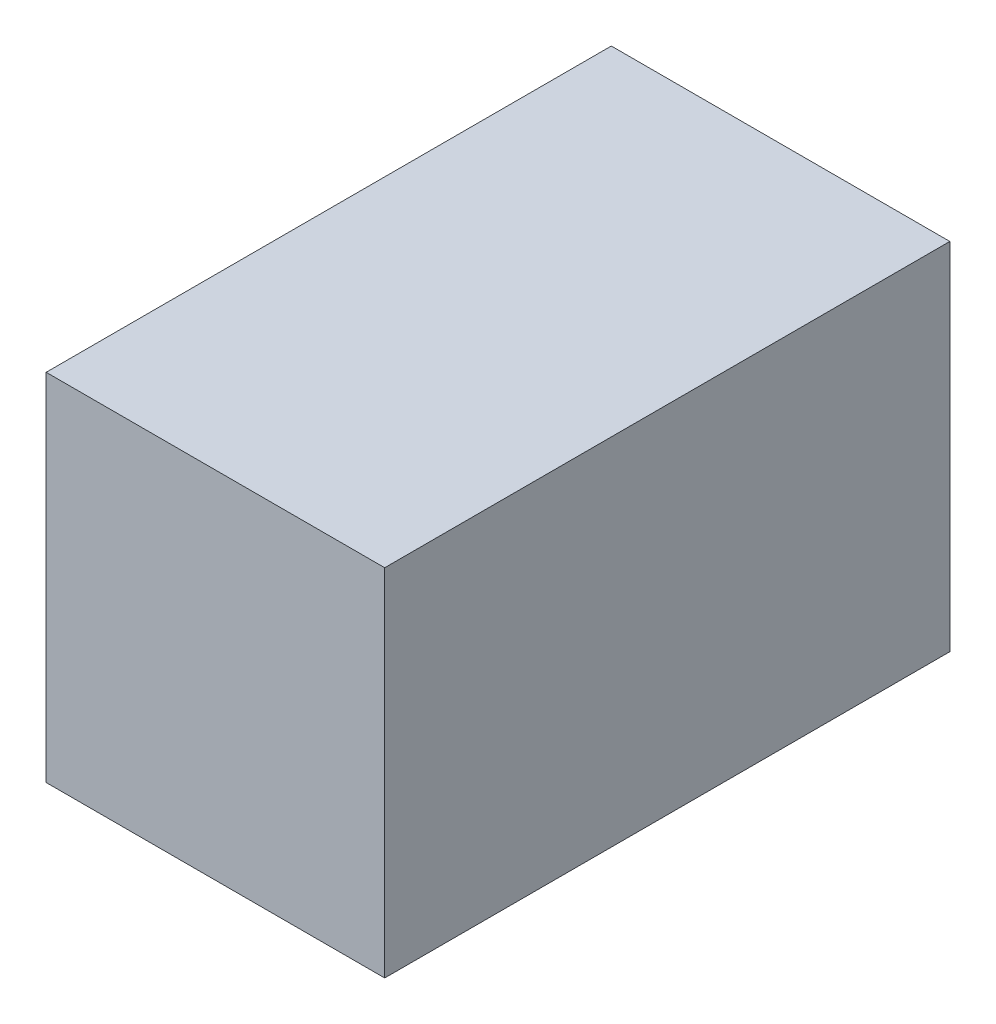
SolidWorks part; units mm, degrees
ref_plane "Front Plane" through (0, 0, 0) normal (0, 0, 1) x (1, 0, 0)
ref_plane "Top Plane" through (0, 0, 0) normal (0, 1, 0) x (1, 0, 0)
ref_plane "Right Plane" through (0, 0, 0) normal (1, 0, 0) x (0, 0, -1)
sketch "Sketch1" plane through (0, 0, 0) normal (0, 1, 0) x (1, 0, 0)
  line L1 (60.5, -101) -> (-60.5, -101)
  line L2 (60.5, -101) -> (60.5, 101)
  line L3 (60.5, 101) -> (-60.5, 101)
  line L4 (-60.5, -101) -> (-60.5, 101)
  line L5 (60.5, -101) -> (-60.5, 101) construction
  line L6 (60.5, 101) -> (-60.5, -101) construction
  point P0 (0, 0)
  dimension "D1" = 202
  dimension "D2" = 121
extrude "Boss-Extrude1" add sketch "Sketch1" along normal blind 127
